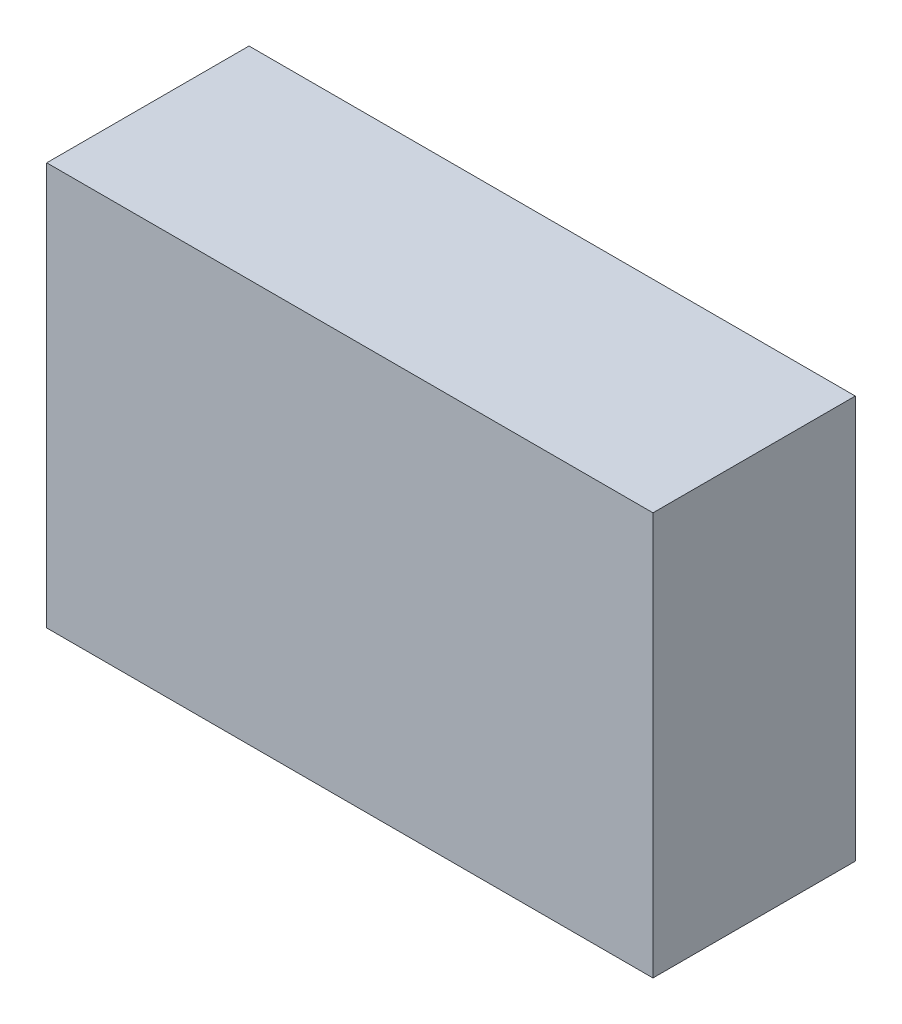
SolidWorks part; units mm, degrees
ref_plane "Plan de face" through (0, 0, 0) normal (0, 0, 1) x (1, 0, 0)
ref_plane "Plan de dessus" through (0, 0, 0) normal (0, 1, 0) x (1, 0, 0)
ref_plane "Plan de droite" through (0, 0, 0) normal (1, 0, 0) x (0, 0, -1)
sketch "Esquisse1" plane through (0, 0, 0) normal (0, 0, 1) x (1, 0, 0)
  line L0 (-1.4984, 1.0084) -> (1.4984, 1.0084)
  line L1 (1.4984, 1.0084) -> (1.4984, -0.983)
  line L2 (1.4984, -0.983) -> (-1.4984, -0.983)
  line L3 (-1.4984, -0.983) -> (-1.4984, 1.0084)
extrude "Component_Outline" add sketch "Esquisse1" along normal blind 1 separate body
sketch3d "Esquisse3D1"
  line L0 (0, 0, 0) -> (1, 0, 0)
  line L1 (0, 0, 0) -> (0, 1, 0)
  line L2 (0, 0, 0) -> (0, 0, 1)
  point P0 (0, 0, 0)
